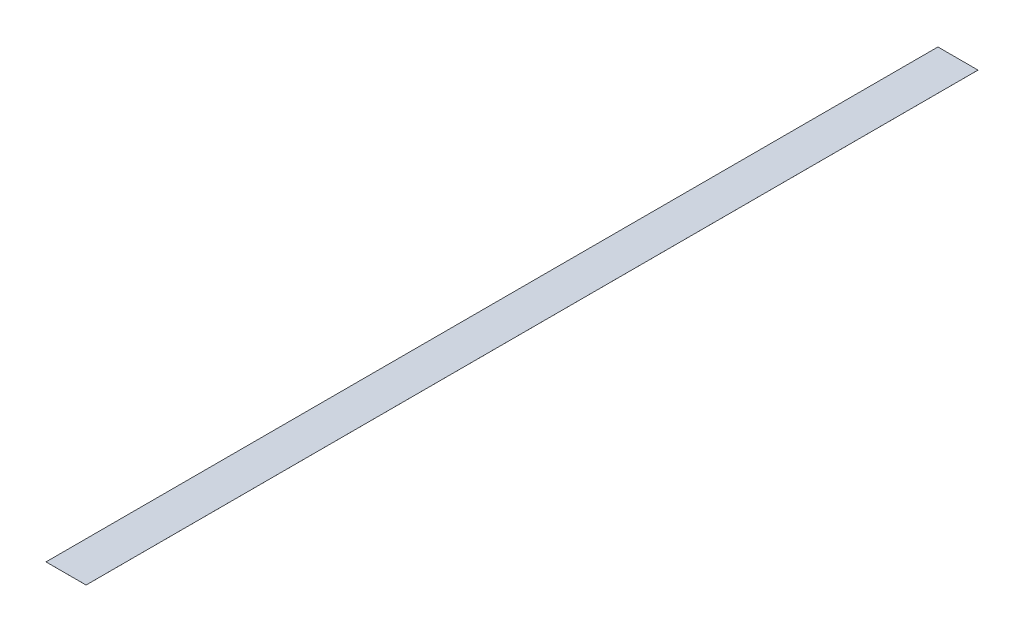
SolidWorks part; units mm, degrees
ref_plane "Plano frontal" through (0, 0, 0) normal (0, 0, 1) x (1, 0, 0)
ref_plane "Plano superior" through (0, 0, 0) normal (0, 1, 0) x (1, 0, 0)
ref_plane "Plano direito" through (0, 0, 0) normal (1, 0, 0) x (0, 0, -1)
sketch "Esboço1" plane through (0, 0, 0) normal (0, 1, 0) x (1, 0, 0)
  line L0 (-1093, 595.536) -> (-1073, 595.536)
  line L1 (0, 0) -> (18.9344, 0)
  line L2 (0, 0) -> (0, 766.8662)
  line L3 (0, 766.8662) -> (18.9344, 766.8662)
  line L4 (18.9344, 0) -> (18.9344, 766.8662)
  line L5 (-381.6968, 766.8662) -> (-362.7624, 766.8662)
  line L6 (-381.6968, 766.8662) -> (-381.6968, 345.536)
  line L7 (-381.6968, 345.536) -> (-362.7624, 345.536)
  line L8 (-362.7624, 766.8662) -> (-362.7624, 345.536)
  line L9 (-858.9344, 645.536) -> (-840, 645.536)
  line L10 (-858.9344, 645.536) -> (-858.9344, 345.536)
  line L11 (-858.9344, 345.536) -> (-840, 345.536)
  line L12 (-840, 645.536) -> (-840, 345.536)
  line L13 (-853.5858, 925.2213) -> (-1253.5858, 925.2213)
  line L14 (-853.5858, 925.2213) -> (-853.5858, 945.2213)
  line L15 (-853.5858, 945.2213) -> (-1253.5858, 945.2213)
  line L16 (-1253.5858, 925.2213) -> (-1253.5858, 945.2213)
  line L17 (-1093, 595.536) -> (-1093, 195.536)
  line L18 (-1093, 195.536) -> (-1073, 195.536)
  line L19 (-1073, 595.536) -> (-1073, 195.536)
  line L21 (-858.9344, 427.7897) -> (-1250.0103, 427.7897)
  line L23 (-858.9344, 407.7897) -> (-1250.0103, 407.7897)
  line L24 (-1250.0103, 427.7897) -> (-1250.0103, 407.7897)
  line L33 (-1439.6613, 239.7512) -> (-1560.0448, 239.7512)
  line L34 (-1439.6613, 239.7512) -> (-1439.6613, 219.7512)
  line L35 (-1439.6613, 219.7512) -> (-1560.0448, 219.7512)
  line L36 (-1560.0448, 239.7512) -> (-1560.0448, 219.7512)
  line L37 (-1627.2015, 576.144) -> (-1607.2015, 576.144)
  line L38 (-1627.2015, 576.144) -> (-1627.2015, 317.0654)
  line L39 (-1627.2015, 317.0654) -> (-1607.2015, 317.0654)
  line L40 (-1607.2015, 576.144) -> (-1607.2015, 317.0654)
  line L41 (-1627.2015, 769.6927) -> (-1607.2015, 769.6927)
  line L42 (-1627.2015, 769.6927) -> (-1627.2015, 1019.6927)
  line L43 (-1627.2015, 1019.6927) -> (-1607.2015, 1019.6927)
  line L44 (-1607.2015, 769.6927) -> (-1607.2015, 1019.6927)
  line L55 (434.4242, 1103.7314) -> (453.3586, 1103.7314)
  line L56 (434.4242, 1103.7314) -> (434.4242, 682.4013)
  line L57 (434.4242, 682.4013) -> (453.3586, 682.4013)
  line L58 (453.3586, 1103.7314) -> (453.3586, 682.4013)
  arc A6 (-381.6968, 766.8662) -> (18.9344, 766.8662) centre (-181.3812, 766.8662) cw
  arc A7 (-362.7624, 766.8662) -> (0, 766.8662) centre (-181.3812, 766.8662) cw
  arc A8 (-362.7624, 345.536) -> (-858.9344, 345.536) centre (-610.8484, 345.536) cw
  arc A9 (-381.6968, 345.536) -> (-840, 345.536) centre (-610.8484, 345.536) cw
  arc A10 (-840, 645.536) -> (-803.6955, 702.0415) centre (-777.8744, 645.536) cw
  arc A11 (-803.6955, 702.0415) -> (-853.5858, 945.2213) centre (-856.6336, 817.8884) ccw
  arc A12 (-858.9344, 645.536) -> (-814.4955, 717.9247) centre (-777.7563, 645.536) cw
  arc A13 (-814.4955, 717.9247) -> (-853.5858, 925.2213) centre (-864.2122, 815.8835) ccw
  arc A14 (-1093, 595.536) -> (-1188.5366, 677.9223) centre (-1176.2913, 595.536) ccw
  arc A15 (-1188.5366, 677.9223) -> (-1354.3411, 742.8189) centre (-1214.8489, 854.9525) cw
  arc A16 (-1354.3411, 742.8189) -> (-1253.5858, 945.2213) centre (-1257.3278, 820.805) cw
  arc A17 (-1073, 595.536) -> (-1188.5366, 698.0004) centre (-1176.2038, 595.536) ccw
  arc A18 (-1188.5366, 698.0004) -> (-1341.8208, 766.8662) centre (-1207.9995, 859.705) cw
  arc A19 (-1341.8208, 766.8662) -> (-1253.5858, 925.2213) centre (-1258.876, 824.4093) cw
  arc A22 (-1368.7558, 309.7722) -> (-1439.6613, 219.7512) centre (-1474.849, 320.402) cw
  arc A23 (-1388.5562, 309.7722) -> (-1439.6613, 239.7512) centre (-1477.6183, 321.1143) cw
  arc A24 (-1388.5562, 309.7722) -> (-1250.0103, 427.7897) centre (-1254.4723, 292.6965) cw
  arc A25 (-1607.2015, 317.0654) -> (-1560.0448, 239.7512) centre (-1520.2441, 317.0654) ccw
  arc A26 (-1627.2015, 317.0654) -> (-1560.0448, 219.7512) centre (-1523.1159, 317.0654) ccw
  arc A27 (-1368.7558, 309.7722) -> (-1250.0103, 407.7897) centre (-1259.9289, 298.8686) cw
extrude "Ressalto-extrusão7" add sketch "Esboço1" along normal blind 0.01 contours L58 L57 L56 L55
